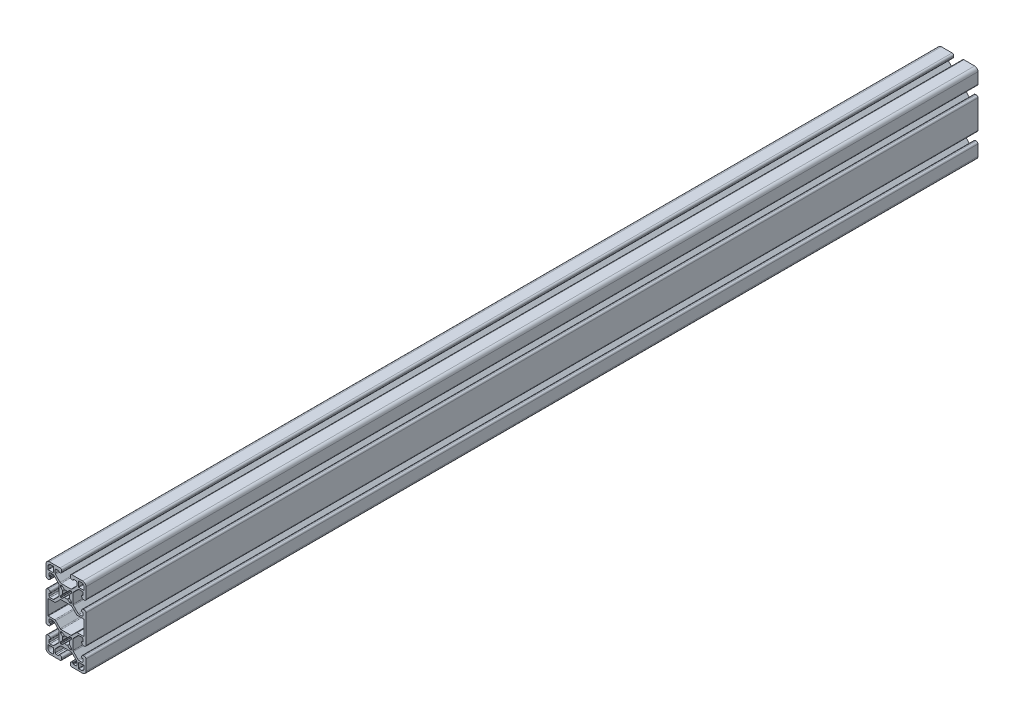
SolidWorks part; units mm, degrees
ref_plane "Front Plane" through (0, 0, 0) normal (0, 0, 1) x (1, 0, 0)
ref_plane "Top Plane" through (0, 0, 0) normal (0, 1, 0) x (1, 0, 0)
ref_plane "Right Plane" through (0, 0, 0) normal (1, 0, 0) x (0, 0, -1)
ref_plane "Plane1" through (0, 0, -304.8) normal (0, 0, -1) x (-1, 0, 0)
sketch "Sketch1" plane through (0, 0, -304.8) normal (0, 0, -1) x (-1, 0, 0)
  line L0 (-16.8656, -11.8618) -> (-12.2428, -11.8618)
  line L1 (-11.8618, -12.2428) -> (-11.8618, -16.8656)
  line L2 (-12.2428, -17.2466) -> (-14.4526, -17.2466)
  line L3 (-17.2466, -14.4526) -> (-17.2466, -12.2428)
  line L4 (-1.5823, -3.1988) -> (-3.2921, -4.9085)
  line L5 (-3.9207, -5.1689) -> (-4.9149, -5.1689)
  line L6 (-5.1689, -4.9149) -> (-5.1689, -3.9207)
  line L7 (-4.9085, -3.2921) -> (-3.1988, -1.5823)
  line L8 (-3.1988, 1.5823) -> (-4.9085, 3.2921)
  line L9 (-5.1689, 3.9207) -> (-5.1689, 4.9149)
  line L10 (-4.9149, 5.1689) -> (-3.9207, 5.1689)
  line L11 (-3.2921, 4.9085) -> (-1.5823, 3.1988)
  line L12 (1.5823, 3.1988) -> (3.2921, 4.9085)
  line L13 (3.9207, 5.1689) -> (4.9149, 5.1689)
  line L14 (5.1689, 4.9149) -> (5.1689, 3.9207)
  line L15 (4.9085, 3.2921) -> (3.1988, 1.5823)
  line L16 (3.1988, -1.5823) -> (4.9085, -3.2921)
  line L17 (5.1689, -3.9207) -> (5.1689, -4.9149)
  line L18 (4.9149, -5.1689) -> (3.9207, -5.1689)
  line L19 (3.2921, -4.9085) -> (1.5823, -3.1988)
  line L20 (16.8656, 49.9618) -> (12.2428, 49.9618)
  line L21 (11.8618, 50.3428) -> (11.8618, 54.9656)
  line L22 (12.2428, 55.3466) -> (14.4526, 55.3466)
  line L23 (17.2466, 52.5526) -> (17.2466, 50.3428)
  line L24 (-12.2428, 49.9618) -> (-16.8656, 49.9618)
  line L25 (-17.2466, 50.3428) -> (-17.2466, 52.5526)
  line L26 (-14.4526, 55.3466) -> (-12.2428, 55.3466)
  line L27 (-11.8618, 54.9656) -> (-11.8618, 50.3428)
  line L28 (-1.5823, 34.9012) -> (-3.2921, 33.1915)
  line L29 (-3.9207, 32.9311) -> (-4.9149, 32.9311)
  line L30 (-5.1689, 33.1851) -> (-5.1689, 34.1793)
  line L31 (-4.9085, 34.8079) -> (-3.1988, 36.5177)
  line L32 (-3.1988, 39.6823) -> (-4.9085, 41.3921)
  line L33 (-5.1689, 42.0207) -> (-5.1689, 43.0149)
  line L34 (-4.9149, 43.2689) -> (-3.9207, 43.2689)
  line L35 (-3.2921, 43.0085) -> (-1.5823, 41.2988)
  line L36 (1.5823, 41.2988) -> (3.2921, 43.0085)
  line L37 (3.9207, 43.2689) -> (4.9149, 43.2689)
  line L38 (5.1689, 43.0149) -> (5.1689, 42.0207)
  line L39 (4.9085, 41.3921) -> (3.1988, 39.6823)
  line L40 (3.1988, 36.5177) -> (4.9085, 34.8079)
  line L41 (5.1689, 34.1793) -> (5.1689, 33.1851)
  line L42 (4.9149, 32.9311) -> (3.9207, 32.9311)
  line L43 (3.2921, 33.1915) -> (1.5823, 34.9012)
  line L44 (17.2466, 25.8572) -> (17.2466, 12.2428)
  line L45 (16.8656, 11.8618) -> (10.8253, 11.8618)
  line L46 (9.9273, 11.4898) -> (5.5531, 7.1157)
  line L47 (4.6551, 6.7437) -> (-4.6551, 6.7437)
  line L48 (-5.5531, 7.1157) -> (-9.9273, 11.4898)
  line L49 (-10.8253, 11.8618) -> (-16.8656, 11.8618)
  line L50 (-17.2466, 12.2428) -> (-17.2466, 25.8572)
  line L51 (-16.8656, 26.2382) -> (-10.8253, 26.2382)
  line L52 (-9.9273, 26.6102) -> (-5.5531, 30.9843)
  line L53 (-4.6551, 31.3563) -> (4.6551, 31.3563)
  line L54 (5.5531, 30.9843) -> (9.9273, 26.6102)
  line L55 (10.8253, 26.2382) -> (16.8656, 26.2382)
  line L56 (12.2428, -11.8618) -> (16.8656, -11.8618)
  line L57 (17.2466, -12.2428) -> (17.2466, -14.4526)
  line L58 (14.4526, -17.2466) -> (12.2428, -17.2466)
  line L59 (11.8618, -16.8656) -> (11.8618, -12.2428)
  line L60 (17.4752, 34.036) -> (16.5608, 34.036)
  line L61 (14.986, 32.4612) -> (14.986, 31.623)
  line L62 (15.367, 31.242) -> (15.6972, 31.242)
  line L63 (16.0782, 30.861) -> (16.0782, 28.702)
  line L64 (15.1892, 27.813) -> (12.3756, 27.813)
  line L65 (11.4776, 28.185) -> (7.1157, 32.5469)
  line L66 (6.7437, 33.4449) -> (6.7437, 42.7551)
  line L67 (7.1157, 43.6531) -> (11.4776, 48.015)
  line L68 (12.3756, 48.387) -> (15.1892, 48.387)
  line L69 (16.0782, 47.498) -> (16.0782, 45.339)
  line L70 (15.6972, 44.958) -> (15.367, 44.958)
  line L71 (14.986, 44.577) -> (14.986, 43.7388)
  line L72 (16.5608, 42.164) -> (17.4752, 42.164)
  line L73 (19.05, 43.7388) -> (19.05, 53.975)
  line L74 (15.875, 57.15) -> (5.6388, 57.15)
  line L75 (4.064, 55.5752) -> (4.064, 54.6608)
  line L76 (5.6388, 53.086) -> (6.477, 53.086)
  line L77 (6.858, 53.467) -> (6.858, 53.7972)
  line L78 (7.239, 54.1782) -> (9.398, 54.1782)
  line L79 (10.287, 53.2892) -> (10.287, 50.4756)
  line L80 (9.915, 49.5776) -> (5.5531, 45.2157)
  line L81 (4.6551, 44.8437) -> (-4.6551, 44.8437)
  line L82 (-5.5531, 45.2157) -> (-9.915, 49.5776)
  line L83 (-10.287, 50.4756) -> (-10.287, 53.2892)
  line L84 (-9.398, 54.1782) -> (-7.239, 54.1782)
  line L85 (-6.858, 53.7972) -> (-6.858, 53.467)
  line L86 (-6.477, 53.086) -> (-5.6388, 53.086)
  line L87 (-4.064, 54.6608) -> (-4.064, 55.5752)
  line L88 (-5.6388, 57.15) -> (-15.875, 57.15)
  line L89 (-19.05, 53.975) -> (-19.05, 43.7388)
  line L90 (-17.4752, 42.164) -> (-16.5608, 42.164)
  line L91 (-14.986, 43.7388) -> (-14.986, 44.577)
  line L92 (-15.367, 44.958) -> (-15.6972, 44.958)
  line L93 (-16.0782, 45.339) -> (-16.0782, 47.498)
  line L94 (-15.1892, 48.387) -> (-12.3756, 48.387)
  line L95 (-11.4776, 48.015) -> (-7.1157, 43.6531)
  line L96 (-6.7437, 42.7551) -> (-6.7437, 33.4449)
  line L97 (-7.1157, 32.5469) -> (-11.4776, 28.185)
  line L98 (-12.3756, 27.813) -> (-15.1892, 27.813)
  line L99 (-16.0782, 28.702) -> (-16.0782, 30.861)
  line L100 (-15.6972, 31.242) -> (-15.367, 31.242)
  line L101 (-14.986, 31.623) -> (-14.986, 32.4612)
  line L102 (-16.5608, 34.036) -> (-17.4752, 34.036)
  line L103 (-19.05, 32.4612) -> (-19.05, 5.6388)
  line L104 (-17.4752, 4.064) -> (-16.5608, 4.064)
  line L105 (-14.986, 5.6388) -> (-14.986, 6.477)
  line L106 (-15.367, 6.858) -> (-15.6972, 6.858)
  line L107 (-16.0782, 7.239) -> (-16.0782, 9.398)
  line L108 (-15.1892, 10.287) -> (-12.3756, 10.287)
  line L109 (-11.4776, 9.915) -> (-7.1157, 5.5531)
  line L110 (-6.7437, 4.6551) -> (-6.7437, -4.6551)
  line L111 (-7.1157, -5.5531) -> (-11.4776, -9.915)
  line L112 (-12.3756, -10.287) -> (-15.1892, -10.287)
  line L113 (-16.0782, -9.398) -> (-16.0782, -7.239)
  line L114 (-15.6972, -6.858) -> (-15.367, -6.858)
  line L115 (-14.986, -6.477) -> (-14.986, -5.6388)
  line L116 (-16.5608, -4.064) -> (-17.4752, -4.064)
  line L117 (-19.05, -5.6388) -> (-19.05, -15.875)
  line L118 (-15.875, -19.05) -> (-5.6388, -19.05)
  line L119 (-4.064, -17.4752) -> (-4.064, -16.5608)
  line L120 (-5.6388, -14.986) -> (-6.477, -14.986)
  line L121 (-6.858, -15.367) -> (-6.858, -15.6972)
  line L122 (-7.239, -16.0782) -> (-9.398, -16.0782)
  line L123 (-10.287, -15.1892) -> (-10.287, -12.3756)
  line L124 (-9.915, -11.4776) -> (-5.5531, -7.1157)
  line L125 (-4.6551, -6.7437) -> (4.6551, -6.7437)
  line L126 (5.5531, -7.1157) -> (9.915, -11.4776)
  line L127 (10.287, -12.3756) -> (10.287, -15.1892)
  line L128 (9.398, -16.0782) -> (7.239, -16.0782)
  line L129 (6.858, -15.6972) -> (6.858, -15.367)
  line L130 (6.477, -14.986) -> (5.6388, -14.986)
  line L131 (4.064, -16.5608) -> (4.064, -17.4752)
  line L132 (5.6388, -19.05) -> (15.875, -19.05)
  line L133 (19.05, -15.875) -> (19.05, -5.6388)
  line L134 (17.4752, -4.064) -> (16.5608, -4.064)
  line L135 (14.986, -5.6388) -> (14.986, -6.477)
  line L136 (15.367, -6.858) -> (15.6972, -6.858)
  line L137 (16.0782, -7.239) -> (16.0782, -9.398)
  line L138 (15.1892, -10.287) -> (12.3756, -10.287)
  line L139 (11.4776, -9.915) -> (7.1157, -5.5531)
  line L140 (6.7437, -4.6551) -> (6.7437, 4.6551)
  line L141 (7.1157, 5.5531) -> (11.4776, 9.915)
  line L142 (12.3756, 10.287) -> (15.1892, 10.287)
  line L143 (16.0782, 9.398) -> (16.0782, 7.239)
  line L144 (15.6972, 6.858) -> (15.367, 6.858)
  line L145 (14.986, 6.477) -> (14.986, 5.6388)
  line L146 (16.5608, 4.064) -> (17.4752, 4.064)
  line L147 (19.05, 5.6388) -> (19.05, 32.4612)
  arc A0 (-12.2428, -11.8618) -> (-11.8618, -12.2428) centre (-12.2428, -12.2428) cw
  arc A1 (-11.8618, -16.8656) -> (-12.2428, -17.2466) centre (-12.2428, -16.8656) cw
  arc A2 (-14.4526, -17.2466) -> (-17.2466, -14.4526) centre (-14.4526, -14.4526) cw
  arc A3 (-17.2466, -12.2428) -> (-16.8656, -11.8618) centre (-16.8656, -12.2428) cw
  arc A4 (1.5823, -3.1988) -> (1.178, -3.1119) centre (1.3129, -3.4682) ccw
  arc A5 (1.178, -3.1119) -> (-1.178, -3.1119) centre (0, 0) cw
  arc A6 (-1.178, -3.1119) -> (-1.5823, -3.1988) centre (-1.3129, -3.4682) ccw
  arc A7 (-3.2921, -4.9085) -> (-3.9207, -5.1689) centre (-3.9207, -4.2799) cw
  arc A8 (-4.9149, -5.1689) -> (-5.1689, -4.9149) centre (-4.9149, -4.9149) cw
  arc A9 (-5.1689, -3.9207) -> (-4.9085, -3.2921) centre (-4.2799, -3.9207) cw
  arc A10 (-3.1988, -1.5823) -> (-3.1119, -1.178) centre (-3.4682, -1.3129) ccw
  arc A11 (-3.1119, -1.178) -> (-3.1119, 1.178) centre (0, 0) cw
  arc A12 (-3.1119, 1.178) -> (-3.1988, 1.5823) centre (-3.4682, 1.3129) ccw
  arc A13 (-4.9085, 3.2921) -> (-5.1689, 3.9207) centre (-4.2799, 3.9207) cw
  arc A14 (-5.1689, 4.9149) -> (-4.9149, 5.1689) centre (-4.9149, 4.9149) cw
  arc A15 (-3.9207, 5.1689) -> (-3.2921, 4.9085) centre (-3.9207, 4.2799) cw
  arc A16 (-1.5823, 3.1988) -> (-1.178, 3.1119) centre (-1.3129, 3.4682) ccw
  arc A17 (-1.178, 3.1119) -> (1.178, 3.1119) centre (0, 0) cw
  arc A18 (1.178, 3.1119) -> (1.5823, 3.1988) centre (1.3129, 3.4682) ccw
  arc A19 (3.2921, 4.9085) -> (3.9207, 5.1689) centre (3.9207, 4.2799) cw
  arc A20 (4.9149, 5.1689) -> (5.1689, 4.9149) centre (4.9149, 4.9149) cw
  arc A21 (5.1689, 3.9207) -> (4.9085, 3.2921) centre (4.2799, 3.9207) cw
  arc A22 (3.1988, 1.5823) -> (3.1119, 1.178) centre (3.4682, 1.3129) ccw
  arc A23 (3.1119, 1.178) -> (3.1119, -1.178) centre (0, 0) cw
  arc A24 (3.1119, -1.178) -> (3.1988, -1.5823) centre (3.4682, -1.3129) ccw
  arc A25 (4.9085, -3.2921) -> (5.1689, -3.9207) centre (4.2799, -3.9207) cw
  arc A26 (5.1689, -4.9149) -> (4.9149, -5.1689) centre (4.9149, -4.9149) cw
  arc A27 (3.9207, -5.1689) -> (3.2921, -4.9085) centre (3.9207, -4.2799) cw
  arc A28 (12.2428, 49.9618) -> (11.8618, 50.3428) centre (12.2428, 50.3428) cw
  arc A29 (11.8618, 54.9656) -> (12.2428, 55.3466) centre (12.2428, 54.9656) cw
  arc A30 (14.4526, 55.3466) -> (17.2466, 52.5526) centre (14.4526, 52.5526) cw
  arc A31 (17.2466, 50.3428) -> (16.8656, 49.9618) centre (16.8656, 50.3428) cw
  arc A32 (-16.8656, 49.9618) -> (-17.2466, 50.3428) centre (-16.8656, 50.3428) cw
  arc A33 (-17.2466, 52.5526) -> (-14.4526, 55.3466) centre (-14.4526, 52.5526) cw
  arc A34 (-12.2428, 55.3466) -> (-11.8618, 54.9656) centre (-12.2428, 54.9656) cw
  arc A35 (-11.8618, 50.3428) -> (-12.2428, 49.9618) centre (-12.2428, 50.3428) cw
  arc A36 (1.5823, 34.9012) -> (1.178, 34.9881) centre (1.3129, 34.6318) ccw
  arc A37 (1.178, 34.9881) -> (-1.178, 34.9881) centre (0, 38.1) cw
  arc A38 (-1.178, 34.9881) -> (-1.5823, 34.9012) centre (-1.3129, 34.6318) ccw
  arc A39 (-3.2921, 33.1915) -> (-3.9207, 32.9311) centre (-3.9207, 33.8201) cw
  arc A40 (-4.9149, 32.9311) -> (-5.1689, 33.1851) centre (-4.9149, 33.1851) cw
  arc A41 (-5.1689, 34.1793) -> (-4.9085, 34.8079) centre (-4.2799, 34.1793) cw
  arc A42 (-3.1988, 36.5177) -> (-3.1119, 36.922) centre (-3.4682, 36.7871) ccw
  arc A43 (-3.1119, 36.922) -> (-3.1119, 39.278) centre (0, 38.1) cw
  arc A44 (-3.1119, 39.278) -> (-3.1988, 39.6823) centre (-3.4682, 39.4129) ccw
  arc A45 (-4.9085, 41.3921) -> (-5.1689, 42.0207) centre (-4.2799, 42.0207) cw
  arc A46 (-5.1689, 43.0149) -> (-4.9149, 43.2689) centre (-4.9149, 43.0149) cw
  arc A47 (-3.9207, 43.2689) -> (-3.2921, 43.0085) centre (-3.9207, 42.3799) cw
  arc A48 (-1.5823, 41.2988) -> (-1.178, 41.2119) centre (-1.3129, 41.5682) ccw
  arc A49 (-1.178, 41.2119) -> (1.178, 41.2119) centre (0, 38.1) cw
  arc A50 (1.178, 41.2119) -> (1.5823, 41.2988) centre (1.3129, 41.5682) ccw
  arc A51 (3.2921, 43.0085) -> (3.9207, 43.2689) centre (3.9207, 42.3799) cw
  arc A52 (4.9149, 43.2689) -> (5.1689, 43.0149) centre (4.9149, 43.0149) cw
  arc A53 (5.1689, 42.0207) -> (4.9085, 41.3921) centre (4.2799, 42.0207) cw
  arc A54 (3.1988, 39.6823) -> (3.1119, 39.278) centre (3.4682, 39.4129) ccw
  arc A55 (3.1119, 39.278) -> (3.1119, 36.922) centre (0, 38.1) cw
  arc A56 (3.1119, 36.922) -> (3.1988, 36.5177) centre (3.4682, 36.7871) ccw
  arc A57 (4.9085, 34.8079) -> (5.1689, 34.1793) centre (4.2799, 34.1793) cw
  arc A58 (5.1689, 33.1851) -> (4.9149, 32.9311) centre (4.9149, 33.1851) cw
  arc A59 (3.9207, 32.9311) -> (3.2921, 33.1915) centre (3.9207, 33.8201) cw
  arc A60 (17.2466, 12.2428) -> (16.8656, 11.8618) centre (16.8656, 12.2428) cw
  arc A61 (10.8253, 11.8618) -> (9.9273, 11.4898) centre (10.8253, 10.5918) ccw
  arc A62 (5.5531, 7.1157) -> (4.6551, 6.7437) centre (4.6551, 8.0137) cw
  arc A63 (-4.6551, 6.7437) -> (-5.5531, 7.1157) centre (-4.6551, 8.0137) cw
  arc A64 (-9.9273, 11.4898) -> (-10.8253, 11.8618) centre (-10.8253, 10.5918) ccw
  arc A65 (-16.8656, 11.8618) -> (-17.2466, 12.2428) centre (-16.8656, 12.2428) cw
  arc A66 (-17.2466, 25.8572) -> (-16.8656, 26.2382) centre (-16.8656, 25.8572) cw
  arc A67 (-10.8253, 26.2382) -> (-9.9273, 26.6102) centre (-10.8253, 27.5082) ccw
  arc A68 (-5.5531, 30.9843) -> (-4.6551, 31.3563) centre (-4.6551, 30.0863) cw
  arc A69 (4.6551, 31.3563) -> (5.5531, 30.9843) centre (4.6551, 30.0863) cw
  arc A70 (9.9273, 26.6102) -> (10.8253, 26.2382) centre (10.8253, 27.5082) ccw
  arc A71 (16.8656, 26.2382) -> (17.2466, 25.8572) centre (16.8656, 25.8572) cw
  arc A72 (16.8656, -11.8618) -> (17.2466, -12.2428) centre (16.8656, -12.2428) cw
  arc A73 (17.2466, -14.4526) -> (14.4526, -17.2466) centre (14.4526, -14.4526) cw
  arc A74 (12.2428, -17.2466) -> (11.8618, -16.8656) centre (12.2428, -16.8656) cw
  arc A75 (11.8618, -12.2428) -> (12.2428, -11.8618) centre (12.2428, -12.2428) cw
  arc A76 (19.05, 32.4612) -> (17.4752, 34.036) centre (17.4752, 32.4612) ccw
  arc A77 (16.5608, 34.036) -> (14.986, 32.4612) centre (16.5608, 32.4612) ccw
  arc A78 (14.986, 31.623) -> (15.367, 31.242) centre (15.367, 31.623) ccw
  arc A79 (15.6972, 31.242) -> (16.0782, 30.861) centre (15.6972, 30.861) cw
  arc A80 (16.0782, 28.702) -> (15.1892, 27.813) centre (15.1892, 28.702) cw
  arc A81 (12.3756, 27.813) -> (11.4776, 28.185) centre (12.3756, 29.083) cw
  arc A82 (7.1157, 32.5469) -> (6.7437, 33.4449) centre (8.0137, 33.4449) cw
  arc A83 (6.7437, 42.7551) -> (7.1157, 43.6531) centre (8.0137, 42.7551) cw
  arc A84 (11.4776, 48.015) -> (12.3756, 48.387) centre (12.3756, 47.117) cw
  arc A85 (15.1892, 48.387) -> (16.0782, 47.498) centre (15.1892, 47.498) cw
  arc A86 (16.0782, 45.339) -> (15.6972, 44.958) centre (15.6972, 45.339) cw
  arc A87 (15.367, 44.958) -> (14.986, 44.577) centre (15.367, 44.577) ccw
  arc A88 (14.986, 43.7388) -> (16.5608, 42.164) centre (16.5608, 43.7388) ccw
  arc A89 (17.4752, 42.164) -> (19.05, 43.7388) centre (17.4752, 43.7388) ccw
  arc A90 (19.05, 53.975) -> (15.875, 57.15) centre (15.875, 53.975) ccw
  arc A91 (5.6388, 57.15) -> (4.064, 55.5752) centre (5.6388, 55.5752) ccw
  arc A92 (4.064, 54.6608) -> (5.6388, 53.086) centre (5.6388, 54.6608) ccw
  arc A93 (6.477, 53.086) -> (6.858, 53.467) centre (6.477, 53.467) ccw
  arc A94 (6.858, 53.7972) -> (7.239, 54.1782) centre (7.239, 53.7972) cw
  arc A95 (9.398, 54.1782) -> (10.287, 53.2892) centre (9.398, 53.2892) cw
  arc A96 (10.287, 50.4756) -> (9.915, 49.5776) centre (9.017, 50.4756) cw
  arc A97 (5.5531, 45.2157) -> (4.6551, 44.8437) centre (4.6551, 46.1137) cw
  arc A98 (-4.6551, 44.8437) -> (-5.5531, 45.2157) centre (-4.6551, 46.1137) cw
  arc A99 (-9.915, 49.5776) -> (-10.287, 50.4756) centre (-9.017, 50.4756) cw
  arc A100 (-10.287, 53.2892) -> (-9.398, 54.1782) centre (-9.398, 53.2892) cw
  arc A101 (-7.239, 54.1782) -> (-6.858, 53.7972) centre (-7.239, 53.7972) cw
  arc A102 (-6.858, 53.467) -> (-6.477, 53.086) centre (-6.477, 53.467) ccw
  arc A103 (-5.6388, 53.086) -> (-4.064, 54.6608) centre (-5.6388, 54.6608) ccw
  arc A104 (-4.064, 55.5752) -> (-5.6388, 57.15) centre (-5.6388, 55.5752) ccw
  arc A105 (-15.875, 57.15) -> (-19.05, 53.975) centre (-15.875, 53.975) ccw
  arc A106 (-19.05, 43.7388) -> (-17.4752, 42.164) centre (-17.4752, 43.7388) ccw
  arc A107 (-16.5608, 42.164) -> (-14.986, 43.7388) centre (-16.5608, 43.7388) ccw
  arc A108 (-14.986, 44.577) -> (-15.367, 44.958) centre (-15.367, 44.577) ccw
  arc A109 (-15.6972, 44.958) -> (-16.0782, 45.339) centre (-15.6972, 45.339) cw
  arc A110 (-16.0782, 47.498) -> (-15.1892, 48.387) centre (-15.1892, 47.498) cw
  arc A111 (-12.3756, 48.387) -> (-11.4776, 48.015) centre (-12.3756, 47.117) cw
  arc A112 (-7.1157, 43.6531) -> (-6.7437, 42.7551) centre (-8.0137, 42.7551) cw
  arc A113 (-6.7437, 33.4449) -> (-7.1157, 32.5469) centre (-8.0137, 33.4449) cw
  arc A114 (-11.4776, 28.185) -> (-12.3756, 27.813) centre (-12.3756, 29.083) cw
  arc A115 (-15.1892, 27.813) -> (-16.0782, 28.702) centre (-15.1892, 28.702) cw
  arc A116 (-16.0782, 30.861) -> (-15.6972, 31.242) centre (-15.6972, 30.861) cw
  arc A117 (-15.367, 31.242) -> (-14.986, 31.623) centre (-15.367, 31.623) ccw
  arc A118 (-14.986, 32.4612) -> (-16.5608, 34.036) centre (-16.5608, 32.4612) ccw
  arc A119 (-17.4752, 34.036) -> (-19.05, 32.4612) centre (-17.4752, 32.4612) ccw
  arc A120 (-19.05, 5.6388) -> (-17.4752, 4.064) centre (-17.4752, 5.6388) ccw
  arc A121 (-16.5608, 4.064) -> (-14.986, 5.6388) centre (-16.5608, 5.6388) ccw
  arc A122 (-14.986, 6.477) -> (-15.367, 6.858) centre (-15.367, 6.477) ccw
  arc A123 (-15.6972, 6.858) -> (-16.0782, 7.239) centre (-15.6972, 7.239) cw
  arc A124 (-16.0782, 9.398) -> (-15.1892, 10.287) centre (-15.1892, 9.398) cw
  arc A125 (-12.3756, 10.287) -> (-11.4776, 9.915) centre (-12.3756, 9.017) cw
  arc A126 (-7.1157, 5.5531) -> (-6.7437, 4.6551) centre (-8.0137, 4.6551) cw
  arc A127 (-6.7437, -4.6551) -> (-7.1157, -5.5531) centre (-8.0137, -4.6551) cw
  arc A128 (-11.4776, -9.915) -> (-12.3756, -10.287) centre (-12.3756, -9.017) cw
  arc A129 (-15.1892, -10.287) -> (-16.0782, -9.398) centre (-15.1892, -9.398) cw
  arc A130 (-16.0782, -7.239) -> (-15.6972, -6.858) centre (-15.6972, -7.239) cw
  arc A131 (-15.367, -6.858) -> (-14.986, -6.477) centre (-15.367, -6.477) ccw
  arc A132 (-14.986, -5.6388) -> (-16.5608, -4.064) centre (-16.5608, -5.6388) ccw
  arc A133 (-17.4752, -4.064) -> (-19.05, -5.6388) centre (-17.4752, -5.6388) ccw
  arc A134 (-19.05, -15.875) -> (-15.875, -19.05) centre (-15.875, -15.875) ccw
  arc A135 (-5.6388, -19.05) -> (-4.064, -17.4752) centre (-5.6388, -17.4752) ccw
  arc A136 (-4.064, -16.5608) -> (-5.6388, -14.986) centre (-5.6388, -16.5608) ccw
  arc A137 (-6.477, -14.986) -> (-6.858, -15.367) centre (-6.477, -15.367) ccw
  arc A138 (-6.858, -15.6972) -> (-7.239, -16.0782) centre (-7.239, -15.6972) cw
  arc A139 (-9.398, -16.0782) -> (-10.287, -15.1892) centre (-9.398, -15.1892) cw
  arc A140 (-10.287, -12.3756) -> (-9.915, -11.4776) centre (-9.017, -12.3756) cw
  arc A141 (-5.5531, -7.1157) -> (-4.6551, -6.7437) centre (-4.6551, -8.0137) cw
  arc A142 (4.6551, -6.7437) -> (5.5531, -7.1157) centre (4.6551, -8.0137) cw
  arc A143 (9.915, -11.4776) -> (10.287, -12.3756) centre (9.017, -12.3756) cw
  arc A144 (10.287, -15.1892) -> (9.398, -16.0782) centre (9.398, -15.1892) cw
  arc A145 (7.239, -16.0782) -> (6.858, -15.6972) centre (7.239, -15.6972) cw
  arc A146 (6.858, -15.367) -> (6.477, -14.986) centre (6.477, -15.367) ccw
  arc A147 (5.6388, -14.986) -> (4.064, -16.5608) centre (5.6388, -16.5608) ccw
  arc A148 (4.064, -17.4752) -> (5.6388, -19.05) centre (5.6388, -17.4752) ccw
  arc A149 (15.875, -19.05) -> (19.05, -15.875) centre (15.875, -15.875) ccw
  arc A150 (19.05, -5.6388) -> (17.4752, -4.064) centre (17.4752, -5.6388) ccw
  arc A151 (16.5608, -4.064) -> (14.986, -5.6388) centre (16.5608, -5.6388) ccw
  arc A152 (14.986, -6.477) -> (15.367, -6.858) centre (15.367, -6.477) ccw
  arc A153 (15.6972, -6.858) -> (16.0782, -7.239) centre (15.6972, -7.239) cw
  arc A154 (16.0782, -9.398) -> (15.1892, -10.287) centre (15.1892, -9.398) cw
  arc A155 (12.3756, -10.287) -> (11.4776, -9.915) centre (12.3756, -9.017) cw
  arc A156 (7.1157, -5.5531) -> (6.7437, -4.6551) centre (8.0137, -4.6551) cw
  arc A157 (6.7437, 4.6551) -> (7.1157, 5.5531) centre (8.0137, 4.6551) cw
  arc A158 (11.4776, 9.915) -> (12.3756, 10.287) centre (12.3756, 9.017) cw
  arc A159 (15.1892, 10.287) -> (16.0782, 9.398) centre (15.1892, 9.398) cw
  arc A160 (16.0782, 7.239) -> (15.6972, 6.858) centre (15.6972, 7.239) cw
  arc A161 (15.367, 6.858) -> (14.986, 6.477) centre (15.367, 6.477) ccw
  arc A162 (14.986, 5.6388) -> (16.5608, 4.064) centre (16.5608, 5.6388) ccw
  arc A163 (17.4752, 4.064) -> (19.05, 5.6388) centre (17.4752, 5.6388) ccw
extrude "Boss-Extrude1" add sketch "Sketch1" against normal blind 850
